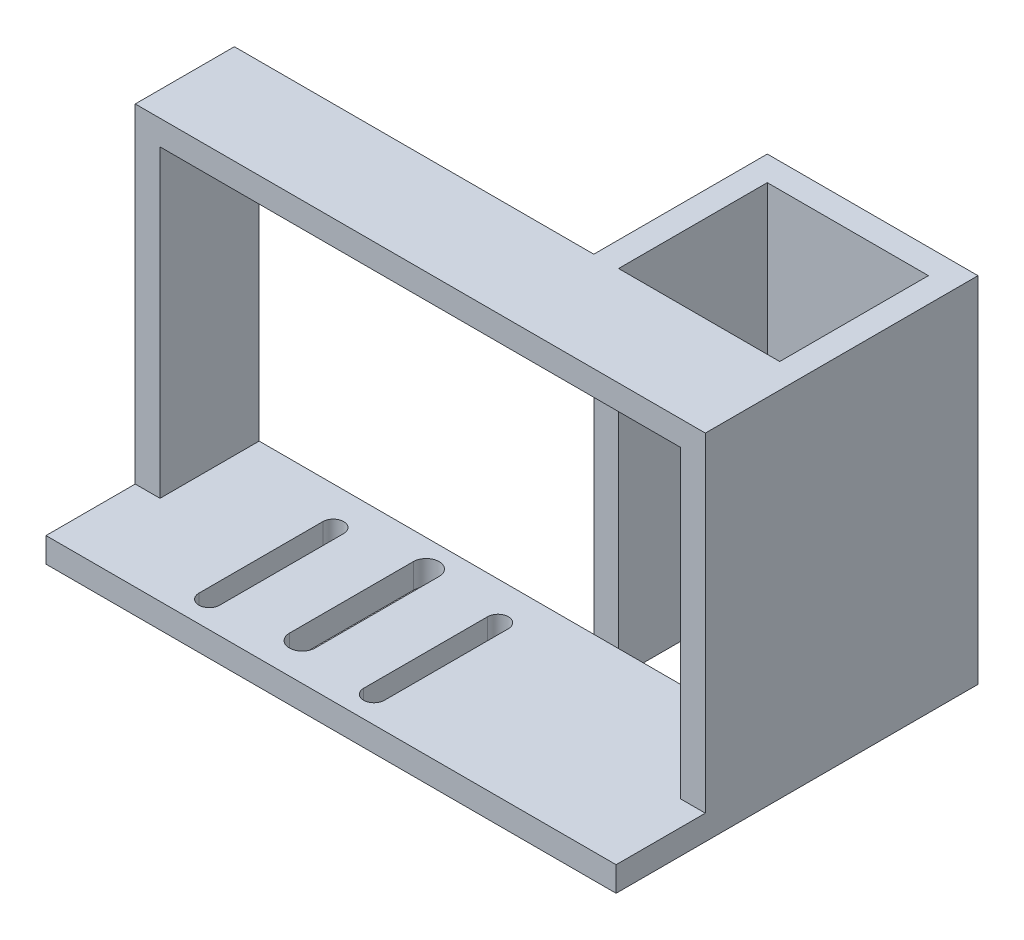
SolidWorks part; units mm, degrees
material "ABS"
ref_plane "Front Plane" through (0, 0, 0) normal (0, 0, 1) x (1, 0, 0)
ref_plane "Top Plane" through (0, 0, 0) normal (0, 1, 0) x (1, 0, 0)
ref_plane "Right Plane" through (0, 0, 0) normal (1, 0, 0) x (0, 0, -1)
sketch "Sketch1" plane through (0, 0, 0) normal (0, 0, 1) x (1, 0, 0)
  line L0 (-66.675, 38.989) -> (66.675, 38.989)
  line L1 (-73.025, -45.339) -> (73.025, -45.339)
  line L2 (-73.025, -45.339) -> (-73.025, 45.339)
  line L3 (-73.025, 45.339) -> (73.025, 45.339)
  line L4 (73.025, -45.339) -> (73.025, 45.339)
  line L5 (-73.025, -45.339) -> (73.025, 45.339) construction
  line L6 (-73.025, 45.339) -> (73.025, -45.339) construction
  line L7 (66.675, -38.989) -> (66.675, 38.989)
  line L8 (-66.675, -38.989) -> (66.675, -38.989)
  line L9 (-66.675, -38.989) -> (-66.675, 38.989)
  point P0 (0, 0)
  dimension "D1" = 146.05
  dimension "D2" = 90.678
  dimension "D3" = 6.35
extrude "Boss-Extrude1" add sketch "Sketch1" along normal blind 25.4
sketch "Sketch2" plane through (0, -45.339, 0) normal (0, 1, 0) x (1, 0, 0)
  line L0 (-66.675, -25.4) -> (66.675, -25.4) construction
  line L1 (-40.513, -25.4) -> (19.812, -25.4)
  line L2 (-40.513, -25.4) -> (-40.513, -48.26)
  line L3 (-40.513, -48.26) -> (19.812, -48.26)
  line L4 (19.812, -25.4) -> (19.812, -48.26)
  line L5 (-73.025, -25.4) -> (-40.513, -48.26)
  line L6 (19.812, -48.26) -> (73.025, -25.4)
  line L7 (73.025, -25.4) -> (19.812, -25.4)
  line L8 (-40.513, -25.4) -> (-73.025, -25.4)
  line L9 (-73.025, -25.4) -> (-73.025, 0) construction
  line L11 (-73.025, -25.4) -> (73.025, -25.4)
  line L12 (-73.025, -25.4) -> (-73.025, -48.26)
  line L13 (-73.025, -48.26) -> (73.025, -48.26)
  line L14 (73.025, -25.4) -> (73.025, -48.26)
  line M7 (73.025, -25.4) -> (-73.025, -25.4)
  dimension "D1" = 22.86
  dimension "D2" = 60.325
  dimension "D3" = 32.512
extrude "Boss-Extrude2" add sketch "Sketch2" along normal up to surface (6.35 mm away) contours L5 L2 M7 | L4 L3 L2 M7 | L6 L4 M7 | L13 L12 L5 | L6 L14 L13 up to face at (0, -38.989, 12.7)
sketch "Sketch5" plane through (0, -38.989, 0) normal (0, 1, 0) x (1, 0, 0)
  line L0 (-16.891, -38.735) -> (-16.891, -6.985) construction
  line L1 (-20.193, -38.735) -> (-20.193, -6.985)
  line L2 (-13.589, -38.735) -> (-13.589, -6.985)
  line L3 (-73.025, -48.26) -> (-73.025, 0) construction
  line L4 (4.2101, -9.7073) -> (4.2101, -41.4573) construction
  line L5 (6.8771, -9.7073) -> (6.8771, -41.4573)
  line L6 (1.5431, -9.7073) -> (1.5431, -41.4573)
  line L7 (-16.891, 0) -> (-16.891, -48.26) construction
  line L8 (-66.675, 0) -> (66.675, 0) construction
  line L9 (-73.025, -48.26) -> (73.025, -48.26) construction
  line L10 (-37.992, -9.7073) -> (-37.992, -41.4573) construction
  line L11 (-40.659, -9.7073) -> (-40.659, -41.4573)
  line L12 (-35.325, -9.7073) -> (-35.325, -41.4573)
  arc A0 (-20.193, -38.735) -> (-13.589, -38.735) centre (-16.891, -38.735) ccw
  arc A1 (-13.589, -6.985) -> (-20.193, -6.985) centre (-16.891, -6.985) ccw
  arc A2 (6.8771, -9.7073) -> (1.5431, -9.7073) centre (4.2101, -9.7073) ccw
  arc A3 (1.5431, -41.4573) -> (6.8771, -41.4573) centre (4.2101, -41.4573) ccw
  arc A4 (-40.659, -9.7073) -> (-35.325, -9.7073) centre (-37.992, -9.7073) cw
  arc A5 (-35.325, -41.4573) -> (-40.659, -41.4573) centre (-37.992, -41.4573) cw
  point P2 (-16.891, -22.86)
  point P11 (4.2101, -25.5823)
  point P24 (-37.992, -25.5823)
  dimension "D1" = 6.604
  dimension "D2" = 31.75
  dimension "D3" = 56.134
  dimension "D4" = 5.334
  dimension "D6" = 21.1011
extrude "Cut-Extrude1" cut sketch "Sketch5" against normal up to next
sketch "Sketch6" plane through (0, 0, 0) normal (0, 0, -1) x (-1, 0, 0)
  line L0 (73.025, -45.339) -> (-73.025, -45.339) construction
  line L1 (-73.025, 45.339) -> (-19.05, 45.339)
  line L2 (-73.025, 45.339) -> (-73.025, -45.339)
  line L3 (-73.025, -45.339) -> (-19.05, -45.339)
  line L4 (-19.05, 45.339) -> (-19.05, -45.339)
  dimension "D1" = 53.975
extrude "Boss-Extrude3" add sketch "Sketch6" along normal blind 44.45
sketch "Sketch7" plane through (19.05, 0, 0) normal (-1, 0, 0) x (0, 0, 1)
  line L0 (0, -38.989) -> (-38.1, -38.989)
  line L1 (-38.1, -38.989) -> (-38.1, 38.989)
  line L2 (-38.1, 38.989) -> (0, 38.989)
  line L3 (0, 38.989) -> (0, -38.989)
  line L5 (-44.45, -45.339) -> (-44.45, 45.339) construction
  dimension "D1" = 6.35
extrude "Cut-Extrude2" [suppressed] cut sketch "Sketch7" against normal up to next
sketch "Sketch8" plane through (0, 45.339, 0) normal (0, 1, 0) x (1, 0, 0)
  line L0 (19.05, 44.45) -> (73.025, 44.45) construction
  line L1 (25.4, 38.1) -> (66.675, 38.1)
  line L2 (25.4, 38.1) -> (25.4, 0)
  line L3 (25.4, 0) -> (66.675, 0)
  line L4 (66.675, 38.1) -> (66.675, 0)
  line L5 (19.05, 44.45) -> (19.05, 0) construction
  line L6 (73.025, -25.4) -> (73.025, 44.45) construction
  line L7 (19.05, 0) -> (-73.025, 0) construction
  dimension "D1" = 6.35
  dimension "D2" = 6.35
  dimension "D3" = 6.35
extrude "Cut-Extrude3" cut sketch "Sketch8" against normal up to next
equation "\"D1@Sketch2\"=1.9in-\"D1@Boss-Extrude1\""
